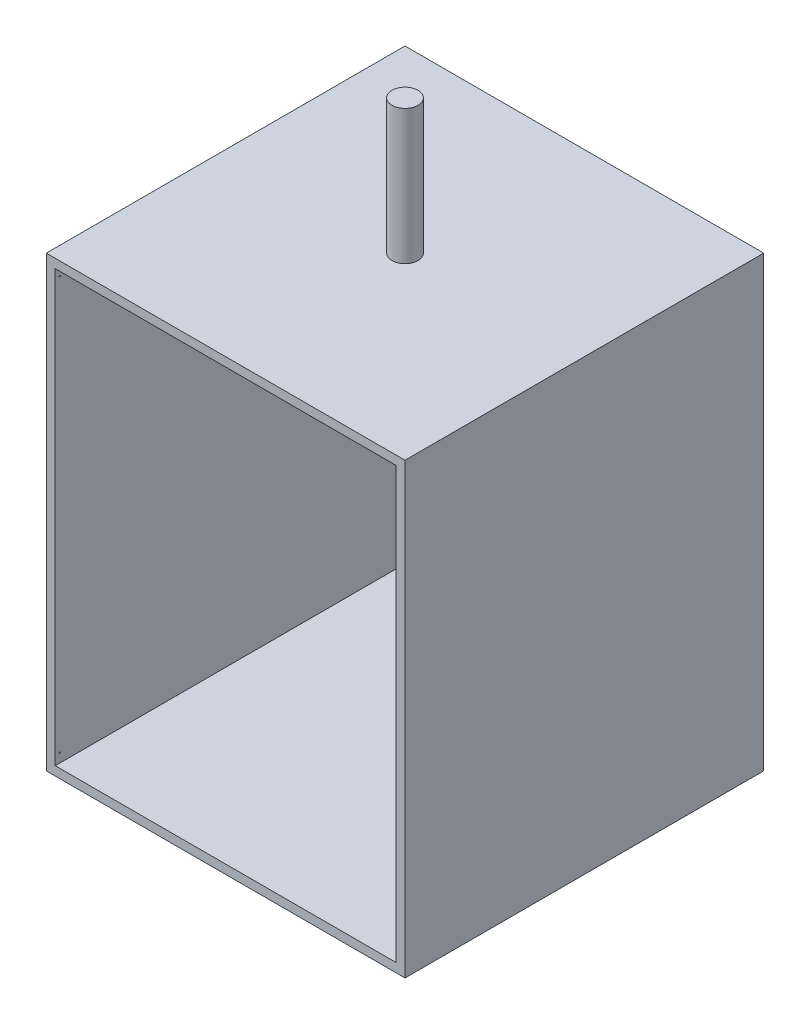
SolidWorks part; units mm, degrees
ref_plane "Front Plane" through (0, 0, 0) normal (0, 0, 1) x (1, 0, 0)
ref_plane "Top Plane" through (0, 0, 0) normal (0, 1, 0) x (1, 0, 0)
ref_plane "Right Plane" through (0, 0, 0) normal (1, 0, 0) x (0, 0, -1)
sketch "Croquis2" plane through (0, 0, 0) normal (0, 0, 1) x (1, 0, 0)
  line L1 (-200, -250) -> (200, -250)
  line L2 (-200, -250) -> (-200, 250)
  line L3 (-200, 250) -> (200, 250)
  line L4 (200, -250) -> (200, 250)
  line L5 (-200, -250) -> (200, 250) construction
  line L6 (-200, 250) -> (200, -250) construction
  point P0 (0, 0)
  dimension "D1" = 400
  dimension "D2" = 500
extrude "Saliente-Extruir1" add sketch "Croquis2" against normal blind 400
sketch "Croquis3" plane through (0, 0, 0) normal (0, 0, 1) x (1, 0, 0)
  line L1 (190, -240) -> (-190, -240)
  line L2 (190, -240) -> (190, 240)
  line L3 (190, 240) -> (-190, 240)
  line L4 (-190, -240) -> (-190, 240)
  line L5 (190, -240) -> (-190, 240) construction
  line L6 (190, 240) -> (-190, -240) construction
  point P0 (0, 0)
extrude "Cortar-Extruir1" cut sketch "Croquis3" against normal blind 395
sketch "Croquis4" plane through (0, 0, -400) normal (0, 0, -1) x (-1, 0, 0)
  line L0 (-200, 250) -> (200, -250) construction
  line L1 (200, 250) -> (-200, -250) construction
  circle A0 centre (0, 0) radius 25.5
  dimension "D1" = 51
extrude "Saliente-Extruir4" add sketch "Croquis4" along normal blind 40
sketch "Croquis5" plane through (0, 0, -440) normal (0, 0, -1) x (-1, 0, 0)
  circle A0 centre (0, 0) radius 25
  dimension "D1" = 50
extrude "Cortar-Extruir2" cut sketch "Croquis5" against normal blind 30
sketch "Croquis6" plane through (0, 250, 0) normal (0, 1, 0) x (1, 0, 0)
  line L0 (200, 0) -> (-200, 400) construction
  line L1 (200, 400) -> (-200, 0) construction
  circle A0 centre (0, 200) radius 14.5
  dimension "D1" = 29
extrude "Saliente-Extruir5" add sketch "Croquis6" along normal blind 150
sketch "Croquis9" plane through (190, 0, 0) normal (-1, 0, 0) x (0, 0, 1)
  line L0 (-5, 240) -> (-5, -240) construction
  line L1 (-395, 240) -> (0, 240) construction
  line L2 (-395, -240) -> (0, -240) construction
  line L3 (-395, -240) -> (-395, 240) construction
  circle A0 centre (-5, 230) radius 0.75
  dimension "D2" = 1.5
  dimension "D1" = 390
  dimension "D3" = 10
extrude "Cortar-Extruir4" cut sketch "Croquis9" against normal blind 1.5
sketch "Croquis10" plane through (-190, 0, 0) normal (1, 0, 0) x (0, 0, -1)
  line L0 (5, -240) -> (5, 240) construction
  line L1 (395, -240) -> (0, -240) construction
  line L2 (395, 240) -> (0, 240) construction
  line L3 (395, 240) -> (395, -240) construction
  circle A0 centre (5, 230) radius 0.75
  dimension "D2" = 1.5
  dimension "D1" = 390
  dimension "D3" = 10
extrude "Cortar-Extruir5" cut sketch "Croquis10" against normal blind 1.5
sketch "Croquis12" plane through (-190, 0, 0) normal (1, 0, 0) x (0, 0, -1)
  line L0 (5, 240) -> (5, -240) construction
  line L1 (395, 240) -> (0, 240) construction
  line L2 (395, -240) -> (0, -240) construction
  line L3 (395, 240) -> (395, -240) construction
  circle A0 centre (5, -230) radius 0.75
  dimension "D2" = 1.5
  dimension "D1" = 390
  dimension "D3" = 10
extrude "Cortar-Extruir6" cut sketch "Croquis12" against normal blind 1.5
sketch "Croquis13" plane through (190, 0, 0) normal (-1, 0, 0) x (0, 0, 1)
  line L0 (-5, 240) -> (-5, -240) construction
  line L1 (-395, 240) -> (0, 240) construction
  line L2 (-395, -240) -> (0, -240) construction
  line L3 (-395, -240) -> (-395, 240) construction
  circle A0 centre (-5, -230) radius 0.75
  dimension "D2" = 1.5
  dimension "D1" = 390
  dimension "D3" = 10
extrude "Cortar-Extruir7" cut sketch "Croquis13" against normal blind 1.5
